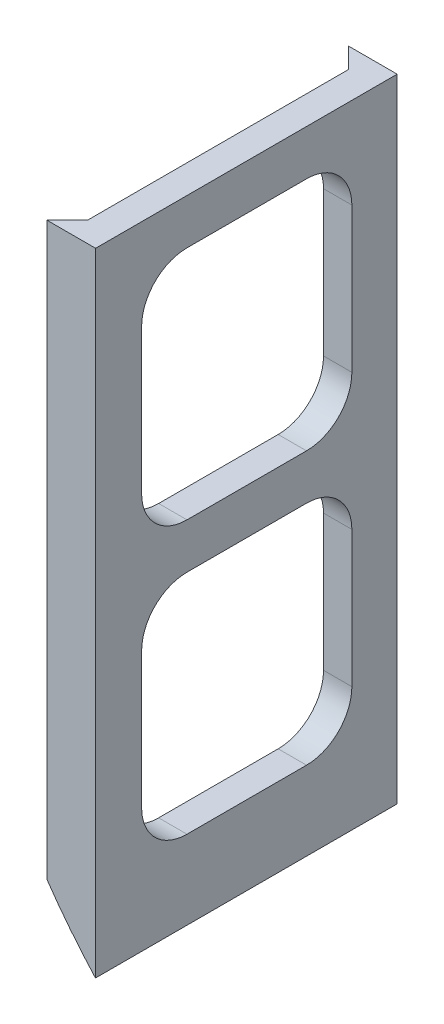
SolidWorks part; units mm, degrees
ref_plane "Plan de face" through (0, 0, 0) normal (0, 0, 1) x (1, 0, 0)
ref_plane "Plan de dessus" through (0, 0, 0) normal (0, 1, 0) x (1, 0, 0)
ref_plane "Plan de droite" through (0, 0, 0) normal (1, 0, 0) x (0, 0, -1)
sketch "Esquisse1" plane through (0, 0, 0) normal (0, 0, 1) x (1, 0, 0)
  line L0 (39.458, 163.9665) -> (39.458, 111.1799)
  line L3 (39.458, 163.9665) -> (41.958, 163.9665)
  line L4 (41.958, 163.9665) -> (41.958, 108.2257)
  arc A17 (39.458, 111.1799) -> (41.958, 108.2257) centre (78.8744, 142.0016) ccw
extrude "Boss.-Extru.1" add sketch "Esquisse1" along normal blind 23
sketch "Esquisse2" plane through (0, 163.9665, 0) normal (0, 1, 0) x (1, 0, 0)
  line L0 (39.458, -11.5) -> (41.958, -11.5) construction
  line L2 (41.958, 1.8) -> (37.658, 1.8)
  line L3 (37.658, 1.8) -> (39.458, 0)
  line L4 (41.958, 0) -> (39.458, 0)
  line L5 (39.458, 0) -> (39.458, -23)
  line L6 (39.458, -23) -> (41.958, -23)
  line L7 (41.958, -23) -> (41.958, 0)
  line L8 (41.958, 0) -> (39.458, 0)
  line L9 (39.458, 0) -> (39.458, -23)
  line L10 (39.458, -23) -> (41.958, -23)
  line L11 (41.958, -23) -> (41.958, 1.8)
  line L13 (37.658, -24.8) -> (39.458, -23)
  line L14 (41.958, -24.8) -> (37.658, -24.8)
  line L15 (41.958, -23) -> (41.958, -24.8)
  dimension "D2" = 45
  dimension "D4" = 1.8
  dimension "D1" = 0
extrude "Boss.-Extru.2" add sketch "Esquisse2" against normal blind 55.74
sketch "Esquisse4" plane through (39.458, 0, 0) normal (-1, 0, 0) x (0, 0, 1)
  line L0 (23, 111.1799) -> (0, 111.1799) construction
  line L1 (6.1961, 159.9665) -> (16.7387, 159.9665)
  line L2 (2.1961, 155.9665) -> (2.1961, 143.1914)
  line L3 (6.1961, 139.1914) -> (16.7387, 139.1914)
  line L4 (20.7387, 155.9665) -> (20.7387, 143.1914)
  line L5 (16.7387, 135.1914) -> (6.1961, 135.1914)
  line L6 (20.7387, 131.1914) -> (20.7387, 119.1799)
  line L7 (16.7387, 115.1799) -> (6.1961, 115.1799)
  line L8 (2.1961, 131.1914) -> (2.1961, 119.1799)
  line L9 (23, 163.9665) -> (0, 163.9665) construction
  arc A0 (20.7387, 119.1799) -> (16.7387, 115.1799) centre (16.7387, 119.1799) cw
  arc A1 (6.1961, 115.1799) -> (2.1961, 119.1799) centre (6.1961, 119.1799) cw
  arc A2 (6.1961, 135.1914) -> (2.1961, 131.1914) centre (6.1961, 131.1914) ccw
  arc A3 (6.1961, 159.9665) -> (2.1961, 155.9665) centre (6.1961, 155.9665) ccw
  arc A4 (2.1961, 143.1914) -> (6.1961, 139.1914) centre (6.1961, 143.1914) ccw
  arc A5 (16.7387, 135.1914) -> (20.7387, 131.1914) centre (16.7387, 131.1914) cw
  arc A6 (16.7387, 139.1914) -> (20.7387, 143.1914) centre (16.7387, 143.1914) ccw
  arc A7 (16.7387, 159.9665) -> (20.7387, 155.9665) centre (16.7387, 155.9665) cw
  dimension "D4" = 4
  dimension "D1" = 4
  dimension "D2" = 4
  dimension "D3" = 4
extrude "Enlèv. mat.-Extru.2" cut sketch "Esquisse4" against normal through all both and the other way through all
sketch "Esquisse5" plane through (0, 0, 24.8) normal (0, 0, 1) x (1, 0, 0)
  line L0 (35.8344, 116.4831) -> (36.3878, 105.7909)
  line L1 (36.3878, 105.7909) -> (45.0502, 105.1024)
  arc A2 (35.8344, 116.4831) -> (45.0502, 105.1024) centre (78.9721, 141.9932) ccw
  ellipse E0 centre (78.6744, 114.5221) end of major axis (78.6744, 141.9993) minor radius 14.0367 (85.934, 138.0392) -> (71.4129, 138.0369) ccw construction
extrude "Enlèv. mat.-Extru.3" cut sketch "Esquisse5" against normal through all both and the other way through all
